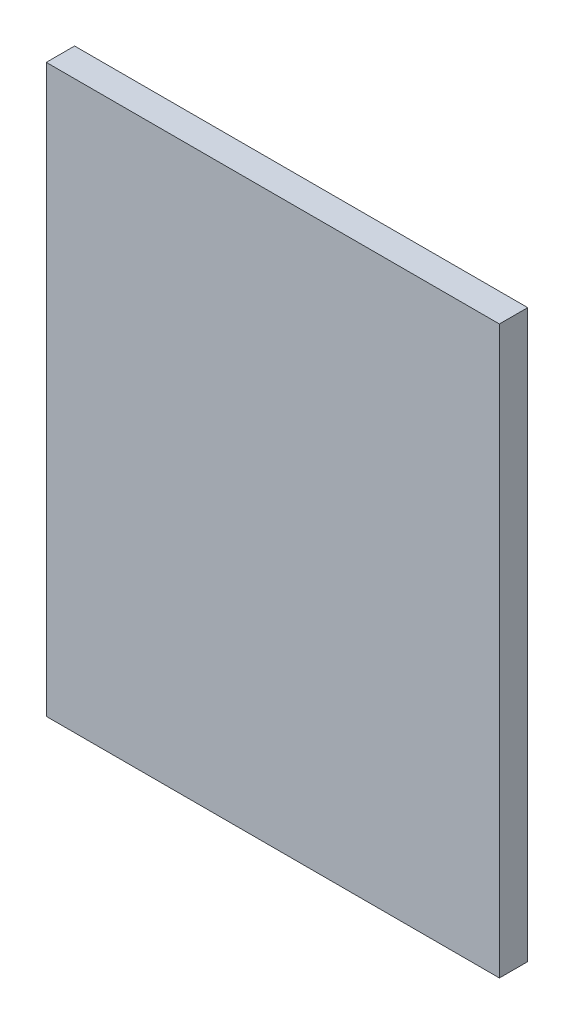
SolidWorks part; units mm, degrees
ref_plane "Plan de face" through (0, 0, 0) normal (0, 0, 1) x (1, 0, 0)
ref_plane "Plan de dessus" through (0, 0, 0) normal (0, 1, 0) x (1, 0, 0)
ref_plane "Plan de droite" through (0, 0, 0) normal (1, 0, 0) x (0, 0, -1)
sketch "Esquisse1" plane through (0, 0, 0) normal (0, 0, 1) x (1, 0, 0)
  line L1 (0, 0) -> (-1.6, 0)
  line L2 (0, 0) -> (0, 2)
  line L3 (0, 2) -> (-1.6, 2)
  line L4 (-1.6, 0) -> (-1.6, 2)
  dimension "D1" = 2
  dimension "D2" = 1.6
extrude "Boss.-Extru.1" add sketch "Esquisse1" along normal blind 0.1
